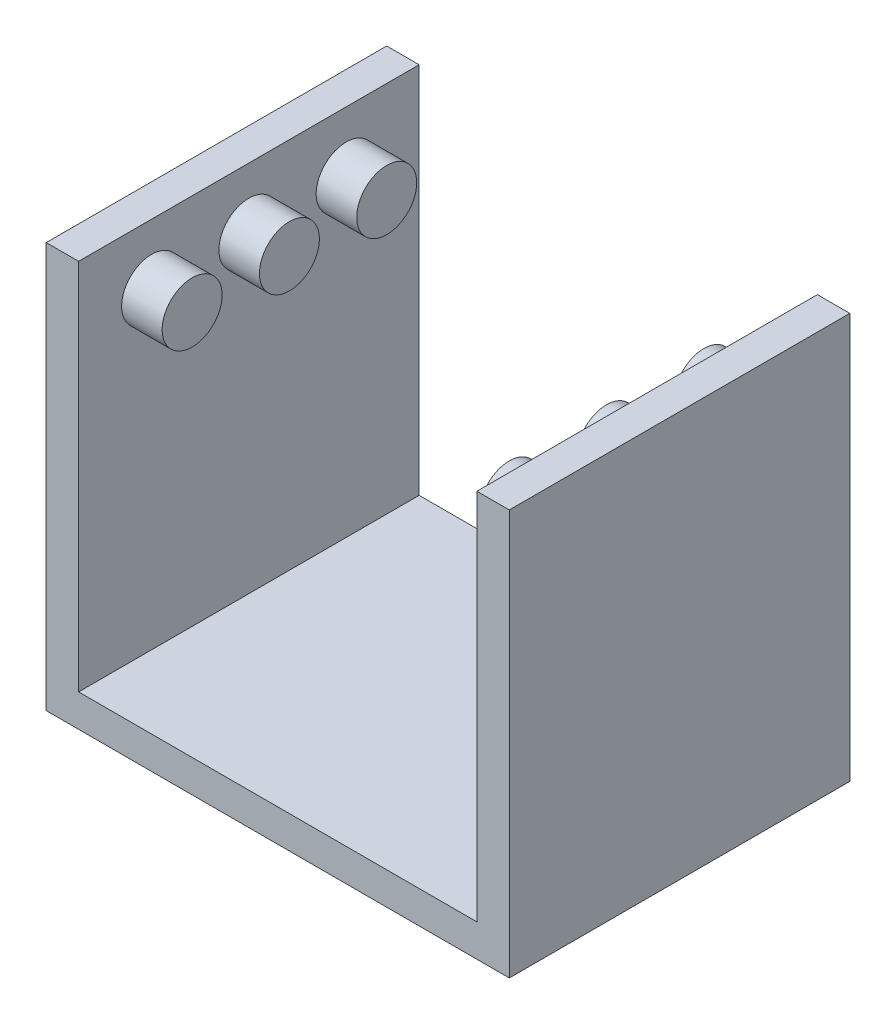
SolidWorks part; units mm, degrees
ref_plane "Front Plane" through (0, 0, 0) normal (0, 0, 1) x (1, 0, 0)
ref_plane "Top Plane" through (0, 0, 0) normal (0, 1, 0) x (1, 0, 0)
ref_plane "Right Plane" through (0, 0, 0) normal (1, 0, 0) x (0, 0, -1)
sketch "Sketch1" plane through (0, 0, 0) normal (0, 0, 1) x (1, 0, 0)
  line L2 (12.3207, -20.272) -> (14.3207, -20.272)
  line L3 (12.3207, -20.272) -> (12.3207, -43.272)
  line L5 (14.3207, -20.272) -> (14.3207, -45.272)
  line L6 (14.3207, -45.272) -> (-14.2395, -45.272)
  line L8 (12.3207, -43.272) -> (-12.2395, -43.272)
  line L11 (-14.2395, -45.272) -> (-14.2395, -20.272)
  line L12 (-14.2395, -20.272) -> (-12.2395, -20.272)
  line L13 (-12.2395, -43.272) -> (-12.2395, -20.272)
  dimension "D1" = 2
  dimension "D2" = 2
  dimension "D3" = 25
  dimension "D4" = 2
  dimension "D5" = 25
extrude "Boss-Extrude4" add sketch "Sketch1" against normal blind 21
sketch "Sketch5" plane through (-12.2395, 0, 0) normal (1, 0, 0) x (0, 0, -1)
  circle A8 centre (10.5, -24) radius 2 construction
  circle A9 centre (10.5, -24) radius 2 construction
  circle A10 centre (4.5, -24) radius 2 construction
  circle A11 centre (4.5, -24) radius 2 construction
  circle A12 centre (16.5, -24) radius 2 construction
  circle A13 centre (16.5, -24) radius 2 construction
  circle A14 centre (16.5, -24) radius 1.85
  circle A15 centre (10.5, -24) radius 1.85
  circle A16 centre (4.5, -24) radius 1.85
  point P12 (10.5, -24.0549)
  point P14 (4.4884, -24)
  dimension "D1" = 3.7
extrude "Boss-Extrude5" add sketch "Sketch5" along normal blind 2.5 separate body
sketch "Sketch6" plane through (12.3207, 0, -12.3207) normal (-1, 0, 0) x (0, 0, 1)
  circle A0 centre (1.8207, -24) radius 1.85 construction
  circle A1 centre (1.8207, -24) radius 1.85 construction
  point P0 (1.8207, -24)
  point P10 (0, 0)
  point P12 (10.5, -24.0549)
  point P14 (4.4884, -24)
  point P15 (0, 0)
  circle B0 centre (1.8207, -24) radius 2 construction
  circle B1 centre (-4.1793, -24) radius 2 construction
  circle B2 centre (7.8207, -24) radius 2 construction
  circle B3 centre (7.8207, -24) radius 1.85
  circle B4 centre (1.8207, -24) radius 1.85
  circle B5 centre (-4.1793, -24) radius 1.85
sketch_block_instance "Block2-1"
sketch_block "Block2" parameters "D1"=3.7, "D2"=3.7
extrude "Boss-Extrude6" add sketch "Sketch6" along normal blind 2.5
